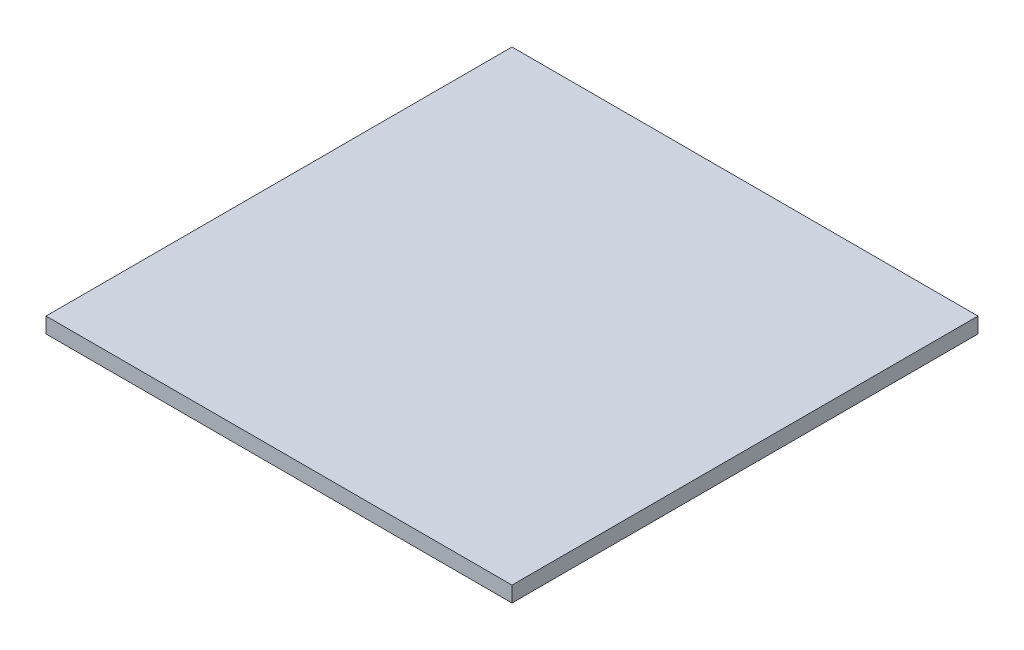
SolidWorks part; units mm, degrees
ref_plane "Front Plane" through (0, 0, 0) normal (0, 0, 1) x (1, 0, 0)
ref_plane "Top Plane" through (0, 0, 0) normal (0, 1, 0) x (1, 0, 0)
ref_plane "Right Plane" through (0, 0, 0) normal (1, 0, 0) x (0, 0, -1)
sketch "Sketch1" plane through (0, 0, 0) normal (0, 1, 0) x (1, 0, 0)
  line L1 (0, 0) -> (762, 0)
  line L2 (0, 0) -> (0, 762)
  line L3 (0, 762) -> (762, 762)
  line L4 (762, 0) -> (762, 762)
  dimension "D1" = 762
  dimension "D2" = 762
extrude "Boss-Extrude1" add sketch "Sketch1" along normal blind 25.4
